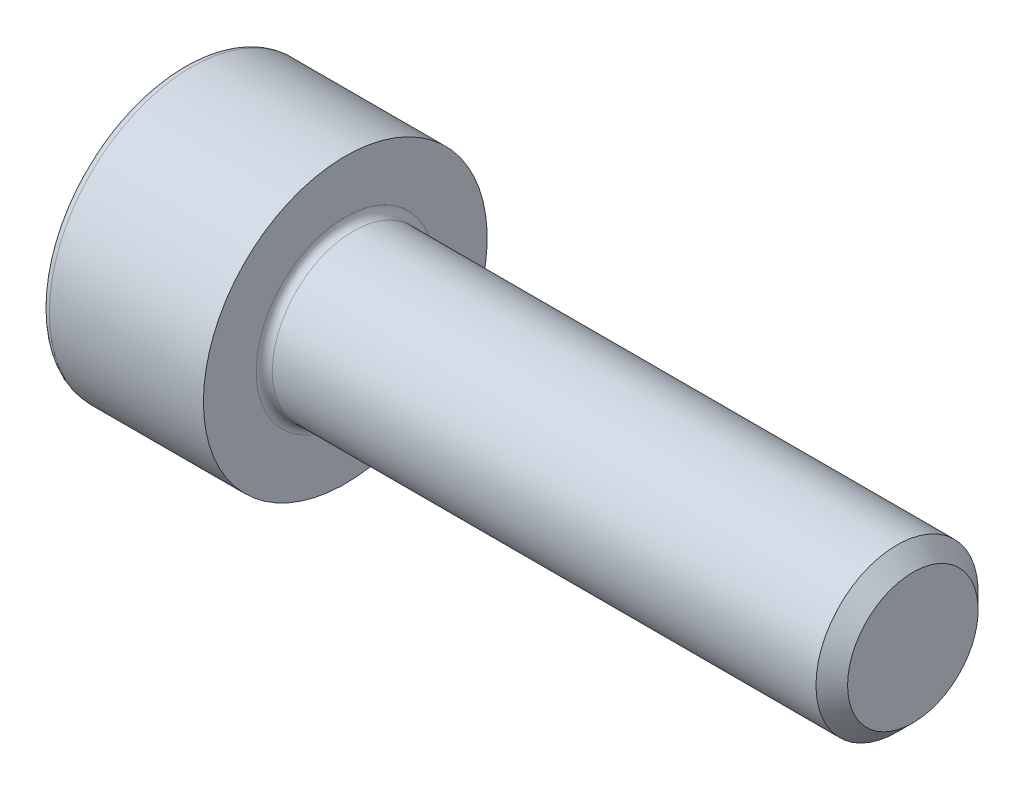
SolidWorks part; units mm, degrees
ref_plane "Face" through (0, 0, 0) normal (0, 0, 1) x (1, 0, 0)
ref_plane "Dessus" through (0, 0, 0) normal (0, 1, 0) x (1, 0, 0)
ref_plane "Droite" through (0, 0, 0) normal (1, 0, 0) x (0, 0, -1)
ref_plane "Plan1" through (0, 0, 0) normal (0, 0, -1) x (-1, 0, 0)
sketch "Esquisse1" plane through (0, 0, 0) normal (0, 0, -1) x (-1, 0, 0)
  line L0 (-4, 3.5) -> (-4, 0)
  line L1 (-4, 0) -> (0, 0)
  line L2 (0, 0) -> (0, 3.5)
  line L3 (0, 3.5) -> (-4, 3.5)
  line L4 (-4, 0) -> (0, 0) construction
revolve "Révolution1" add sketch "Esquisse1" angle 360 about L4
sketch "Esquisse2" plane through (4, 0, 0) normal (1, 0, 0) x (0, 0, -1)
  circle A0 centre (0, 0) radius 2
extrude "Boss.-Extru.1" add sketch "Esquisse2" along normal blind 14
sketch "Esquisse3" plane through (0, 0, 0) normal (-1, 0, 0) x (0, 0, 1)
  line L0 (0, -1.773) -> (1.5355, -0.8865)
  line L1 (1.5355, -0.8865) -> (1.5355, 0.8865)
  line L2 (1.5355, 0.8865) -> (0, 1.773)
  line L3 (0, 1.773) -> (-1.5355, 0.8865)
  line L4 (-1.5355, 0.8865) -> (-1.5355, -0.8865)
  line L5 (-1.5355, -0.8865) -> (0, -1.773)
extrude "Enlèv. mat.-Extru.1" cut sketch "Esquisse3" against normal blind 2
sketch "Esquisse4" plane through (0, 0, 0) normal (0, 0, 1) x (1, 0, 0)
  line L0 (2, 1.5355) -> (2, 0)
  line L1 (2, 0) -> (2.8865, 0)
  line L2 (2.8865, 0) -> (2, 1.5355)
  line L3 (2, 0) -> (2.8865, 0) construction
revolve "Enlèvement de matière-Révolution1" cut sketch "Esquisse4" angle 360 about L3
chamfer "Chanfrein1" distance 0.39 angle 45 1 edges at (18, 0, -2)
fillet "Congé1" radius 0.2 2 edges at (0, 0, 3.5) (4, 0, -2)
